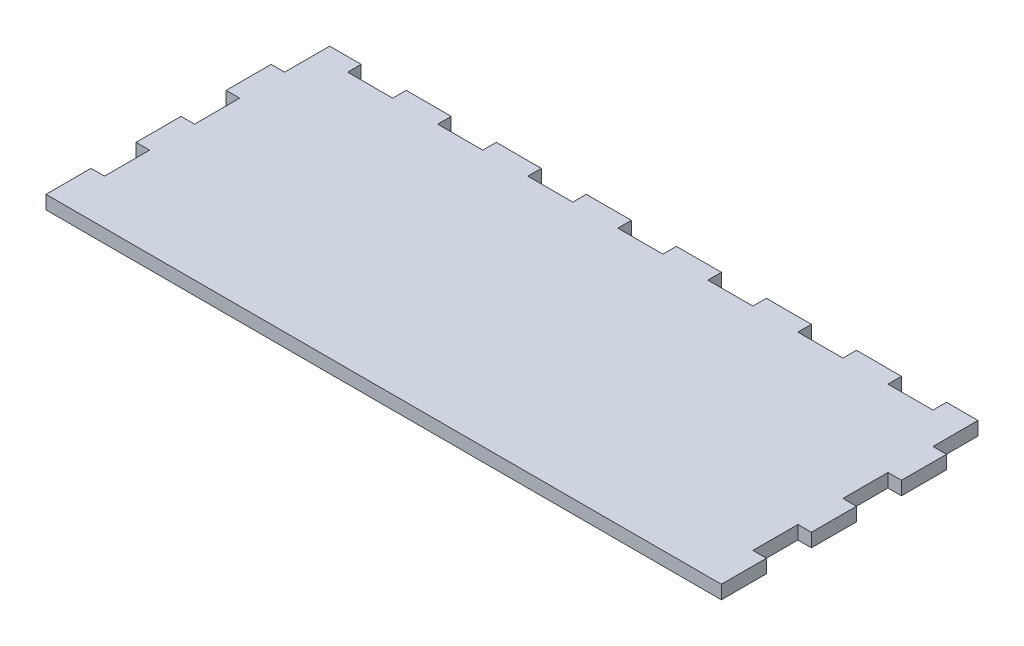
SolidWorks part; units mm, degrees
ref_plane "Front Plane" through (0, 0, 0) normal (0, 0, 1) x (1, 0, 0)
ref_plane "Top Plane" through (0, 0, 0) normal (0, 1, 0) x (1, 0, 0)
ref_plane "Right Plane" through (0, 0, 0) normal (1, 0, 0) x (0, 0, -1)
sketch "Sketch1" plane through (0, 0, 0) normal (0, 1, 0) x (1, 0, 0)
  line L1 (-75, -30) -> (75, -30)
  line L2 (-75, -30) -> (-75, 30)
  line L3 (-75, 30) -> (75, 30)
  line L4 (75, -30) -> (75, 30)
  line L5 (-75, -30) -> (75, 30) construction
  line L6 (-75, 30) -> (75, -30) construction
  point P0 (0, 0)
  dimension "D1" = 150
  dimension "D2" = 60
extrude "Boss-Extrude1" add sketch "Sketch1" along normal blind 3
sketch "Sketch2" plane through (0, 3, 0) normal (0, 1, 0) x (1, 0, 0)
  line L0 (75, -30) -> (75, 30) construction
  line L1 (75, -10) -> (72, -10)
  line L2 (75, -10) -> (75, -20)
  line L3 (75, -20) -> (72, -20)
  line L4 (72, -10) -> (72, -20)
  line L5 (-75, -30) -> (75, -30) construction
  dimension "D1" = 10
  dimension "D2" = 10
  dimension "D3" = 3
extrude "Cut-Extrude1" cut sketch "Sketch2" against normal through all
pattern_linear "LPattern1" count 3 spacing 20 along (0, 0, -1) of "Cut-Extrude1"
mirror "Mirror1" about plane through (0, 0, 0) normal (1, 0, 0) of "LPattern1", "Cut-Extrude1"
sketch "Sketch3" plane through (0, 3, 0) normal (0, 1, 0) x (1, 0, 0)
  line L0 (72, 30) -> (-72, 30) construction
  line L1 (-65, 30) -> (-55, 30)
  line L2 (-65, 30) -> (-65, 27)
  line L3 (-65, 27) -> (-55, 27)
  line L4 (-55, 30) -> (-55, 27)
  line L5 (-75, 20) -> (-75, 10) construction
  dimension "D1" = 10
  dimension "D2" = 10
  dimension "D3" = 3
extrude "Cut-Extrude2" cut sketch "Sketch3" against normal through all
pattern_linear "LPattern2" count 7 spacing 20 along (1, 0, 0) of "Cut-Extrude2"
